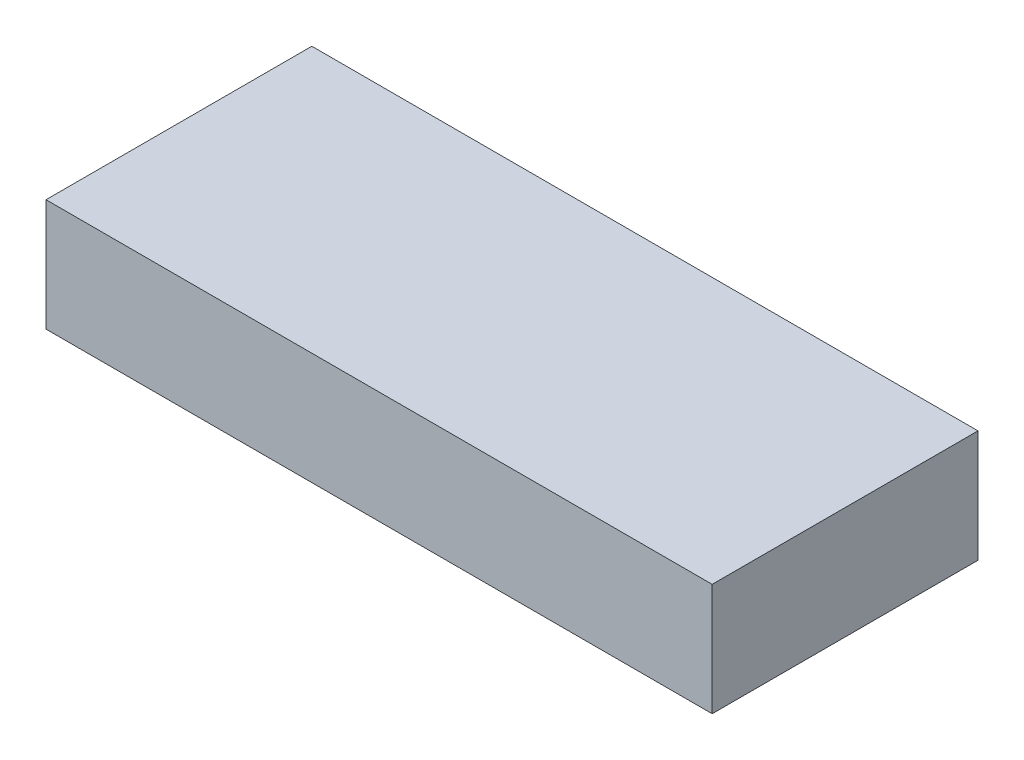
SolidWorks part; units mm, degrees
ref_plane "Front Plane" through (0, 0, 0) normal (0, 0, 1) x (1, 0, 0)
ref_plane "Top Plane" through (0, 0, 0) normal (0, 1, 0) x (1, 0, 0)
ref_plane "Right Plane" through (0, 0, 0) normal (1, 0, 0) x (0, 0, -1)
sketch "Sketch1" plane through (0, 0, 0) normal (0, 1, 0) x (1, 0, 0)
  line L1 (0, 0) -> (41.6, 0)
  line L2 (0, 0) -> (0, 16.6)
  line L3 (0, 16.6) -> (41.6, 16.6)
  line L4 (41.6, 0) -> (41.6, 16.6)
  dimension "D1" = 41.6
  dimension "D2" = 16.6
extrude "Boss-Extrude1" add sketch "Sketch1" along normal blind 7
